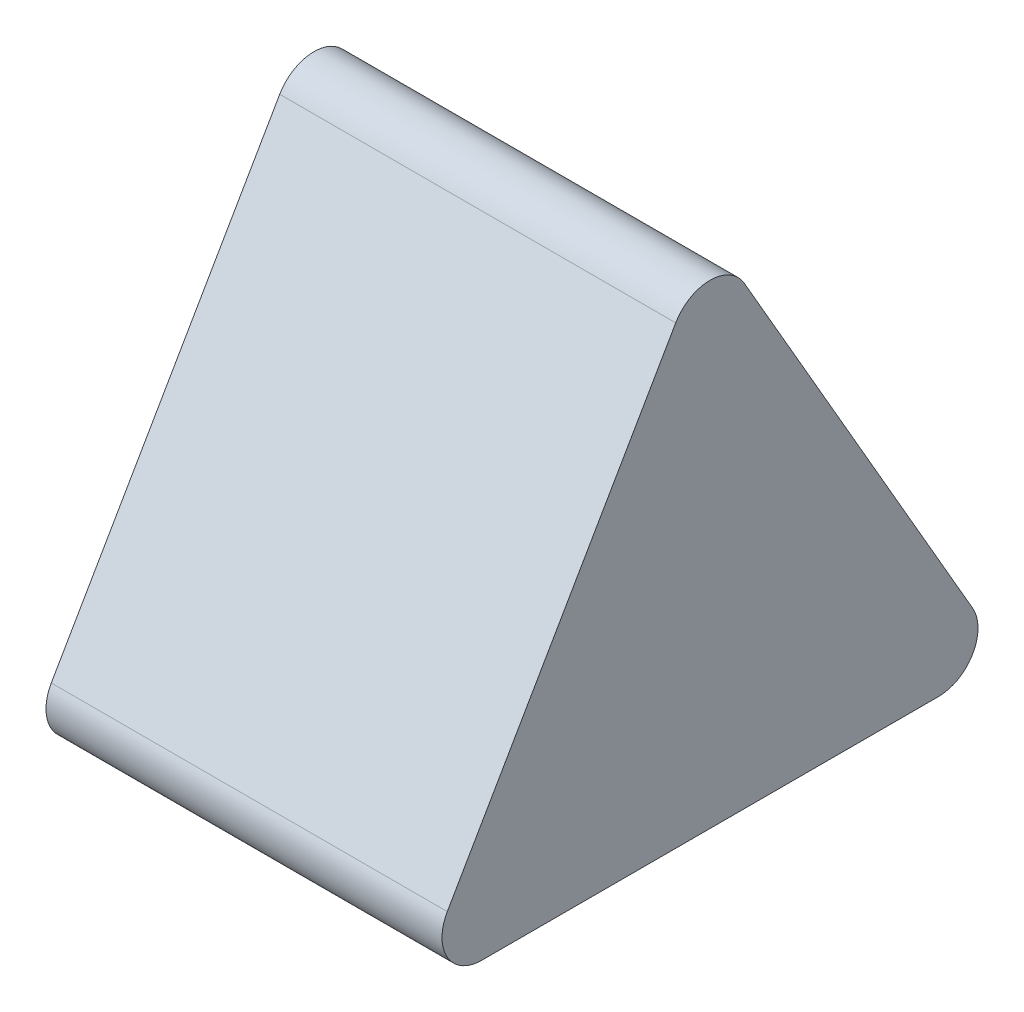
SolidWorks part; units mm, degrees
ref_plane "前视基准面" through (0, 0, 0) normal (0, 0, 1) x (1, 0, 0)
ref_plane "上视基准面" through (0, 0, 0) normal (0, 1, 0) x (1, 0, 0)
ref_plane "右视基准面" through (0, 0, 0) normal (1, 0, 0) x (0, 0, -1)
sketch "草图1" plane through (0, 0, 0) normal (1, 0, 0) x (0, 0, -1)
  line L0 (-15, 0) -> (15, 0)
  line L1 (15, 0) -> (0, 25.9808)
  line L2 (0, 25.9808) -> (0, 0)
  line L3 (-15, 0) -> (0, 25.9808)
  dimension "D1" = 30
  dimension "D2" = 30
extrude "凸台-拉伸1" add sketch "草图1" along normal blind 20 contours L1 L2 L0 | L3 L0 L2
fillet "圆角1" radius 2 3 edges at (10, 25.9808, 0) (10, 0, -15) (10, 0, 15)
